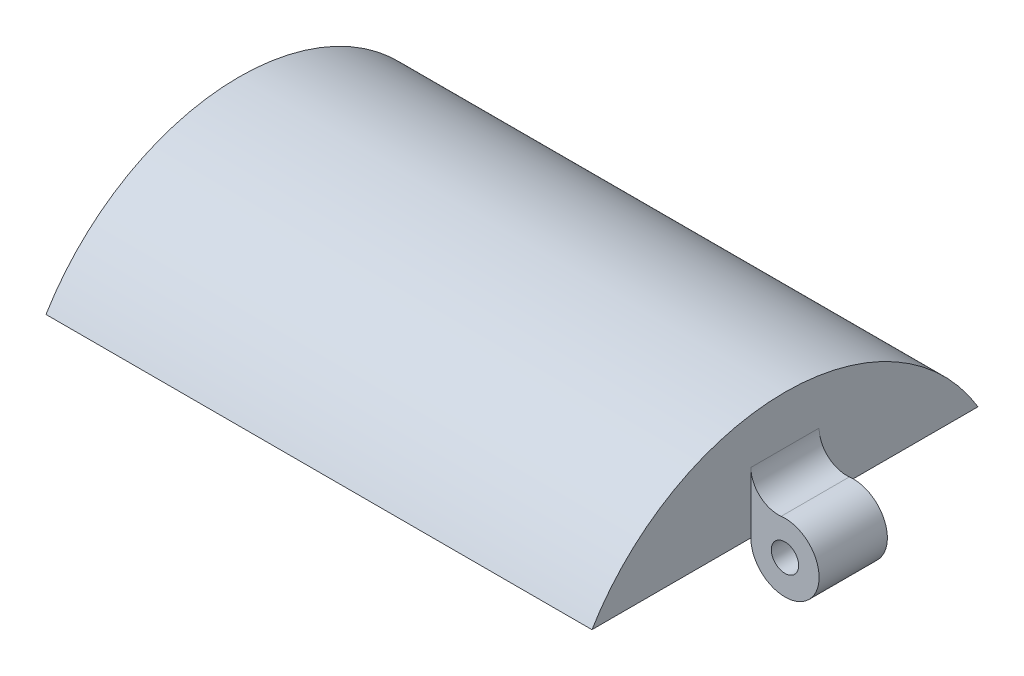
SolidWorks part; units mm, degrees
ref_plane "Front Plane" through (0, 0, 0) normal (0, 0, 1) x (1, 0, 0)
ref_plane "Top Plane" through (0, 0, 0) normal (0, 1, 0) x (1, 0, 0)
ref_plane "Right Plane" through (0, 0, 0) normal (1, 0, 0) x (0, 0, -1)
sketch "Sketch2" plane through (0, 0, 0) normal (1, 0, 0) x (0, 0, -1)
  circle A0 centre (0, 0) radius 16.5
extrude "Boss-Extrude1" add sketch "Sketch2" along normal blind 40
sketch "Sketch3" plane through (0, 0, 0) normal (-1, 0, 0) x (0, 0, 1)
  line L1 (-16.5, 8.5) -> (16.5, 8.5)
  line L2 (-16.5, 8.5) -> (-16.5, -16.5)
  line L3 (-16.5, -16.5) -> (16.5, -16.5)
  line L4 (16.5, 8.5) -> (16.5, -16.5)
  circle A0 centre (0, 0) radius 16.5 construction
  dimension "D1" = 8.5
extrude "Cut-Extrude1" cut sketch "Sketch3" against normal blind 40
sketch "Sketch4" plane through (0, 8.5, 0) normal (0, -1, 0) x (1, 0, 0)
  line L0 (0, 14.1421) -> (40, 14.1421) construction
  line L1 (2, 12.1421) -> (38, 12.1421)
  line L2 (2, 12.1421) -> (2, -12.1421)
  line L3 (2, -12.1421) -> (38, -12.1421)
  line L4 (38, 12.1421) -> (38, -12.1421)
  line L9 (40, 14.1421) -> (40, -14.1421) construction
  line L10 (0, -14.1421) -> (0, 14.1421) construction
  line L11 (40, -14.1421) -> (0, -14.1421) construction
  dimension "D5" = 2
  dimension "D6" = 2
  dimension "D7" = 2
  dimension "D8" = 2
extrude "Cut-Extrude2" cut sketch "Sketch4" against normal offset from surface (1.1342 mm away) 1
sketch "Sketch5" plane through (0, 8.5, 0) normal (0, -1, 0) x (1, 0, 0)
  line L9 (2, 12.1421) -> (2, -12.1421) construction
  line L10 (2, 12.1421) -> (2, -12.1421)
  line L11 (38, 12.1421) -> (2, 12.1421) construction
  line L12 (38, 12.1421) -> (2, 12.1421)
  line L13 (38, 12.1421) -> (38, -12.1421) construction
  line L14 (38, 12.1421) -> (38, -12.1421)
  line L15 (38, -12.1421) -> (2, -12.1421) construction
  line L16 (38, -12.1421) -> (2, -12.1421)
  line L17 (0, -14.1421) -> (0, 14.1421) construction
  line L18 (1.5, 12.6421) -> (38.5, 12.6421)
  line L19 (1.5, 12.6421) -> (1.5, -12.6421)
  line L20 (1.5, -12.6421) -> (38.5, -12.6421)
  line L21 (38.5, 12.6421) -> (38.5, -12.6421)
  line L22 (0, 14.1421) -> (40, 14.1421) construction
  line L23 (40, 14.1421) -> (40, -14.1421) construction
  line L24 (40, -14.1421) -> (0, -14.1421) construction
  dimension "D1" = 1.5
  dimension "D2" = 1.5
  dimension "D3" = 1.5
  dimension "D4" = 1.5
extrude "Boss-Extrude2" add sketch "Sketch5" along normal blind 1.5
ref_plane "Plane1" through (0, 0, 0) normal (0, 0, 1) x (1, 0, 0)
sketch "Sketch6" plane through (40, 0, 0) normal (1, 0, 0) x (0, 0, -1)
  line L0 (0, 8.5) -> (0, 16.5) construction
  line L1 (-14.1421, 8.5) -> (14.1421, 8.5) construction
  arc A0 (14.1421, 8.5) -> (-14.1421, 8.5) centre (0, 0) ccw construction
sketch "Sketch7" plane through (0, 0, 0) normal (0, 0, 1) x (1, 0, 0)
  line L0 (40, 8.5) -> (45, 8.5) construction
  line L1 (40, 8.5) -> (40, 12.9721)
  line L2 (40, 8.5) -> (40, 16.5) construction
  arc A0 (40, 8.5) -> (42.2222, 10.9845) centre (42.5, 8.5) ccw
  circle A1 centre (42.5, 8.5) radius 1
  arc A2 (40, 12.9721) -> (42.2222, 10.9845) centre (42, 12.9721) ccw
  dimension "D1" = 2
  dimension "D2" = 5
  dimension "D3" = 2
extrude "Boss-Extrude3" add sketch "Sketch7" along normal mid plane 5
ref_plane "Plane2" through (20, 0, 0) normal (1, 0, 0) x (0, 0, -1)
mirror "Mirror2" about plane through (20, 0, 0) normal (1, 0, 0) of "Boss-Extrude3"
